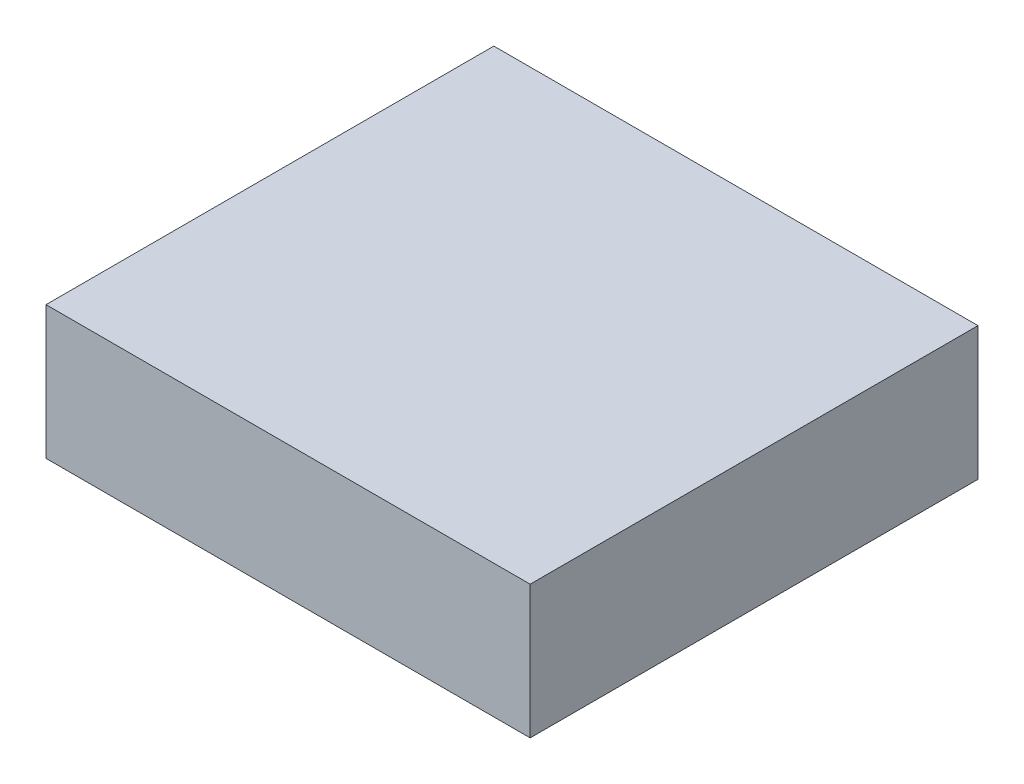
SolidWorks part; units mm, degrees
ref_plane "Front Plane" through (0, 0, 0) normal (0, 0, 1) x (1, 0, 0)
ref_plane "Top Plane" through (0, 0, 0) normal (0, 1, 0) x (1, 0, 0)
ref_plane "Right Plane" through (0, 0, 0) normal (1, 0, 0) x (0, 0, -1)
sketch "Sketch1" plane through (0, 0, 0) normal (0, 1, 0) x (1, 0, 0)
  line L1 (-50.8, 46.99) -> (50.8, 46.99)
  line L2 (-50.8, 46.99) -> (-50.8, -46.99)
  line L3 (-50.8, -46.99) -> (50.8, -46.99)
  line L4 (50.8, 46.99) -> (50.8, -46.99)
  line L5 (-50.8, 46.99) -> (50.8, -46.99) construction
  line L6 (-50.8, -46.99) -> (50.8, 46.99) construction
  point P0 (0, 0)
  dimension "D1" = 101.6
  dimension "D2" = 93.98
extrude "Boss-Extrude1" add sketch "Sketch1" along normal blind 27.94
